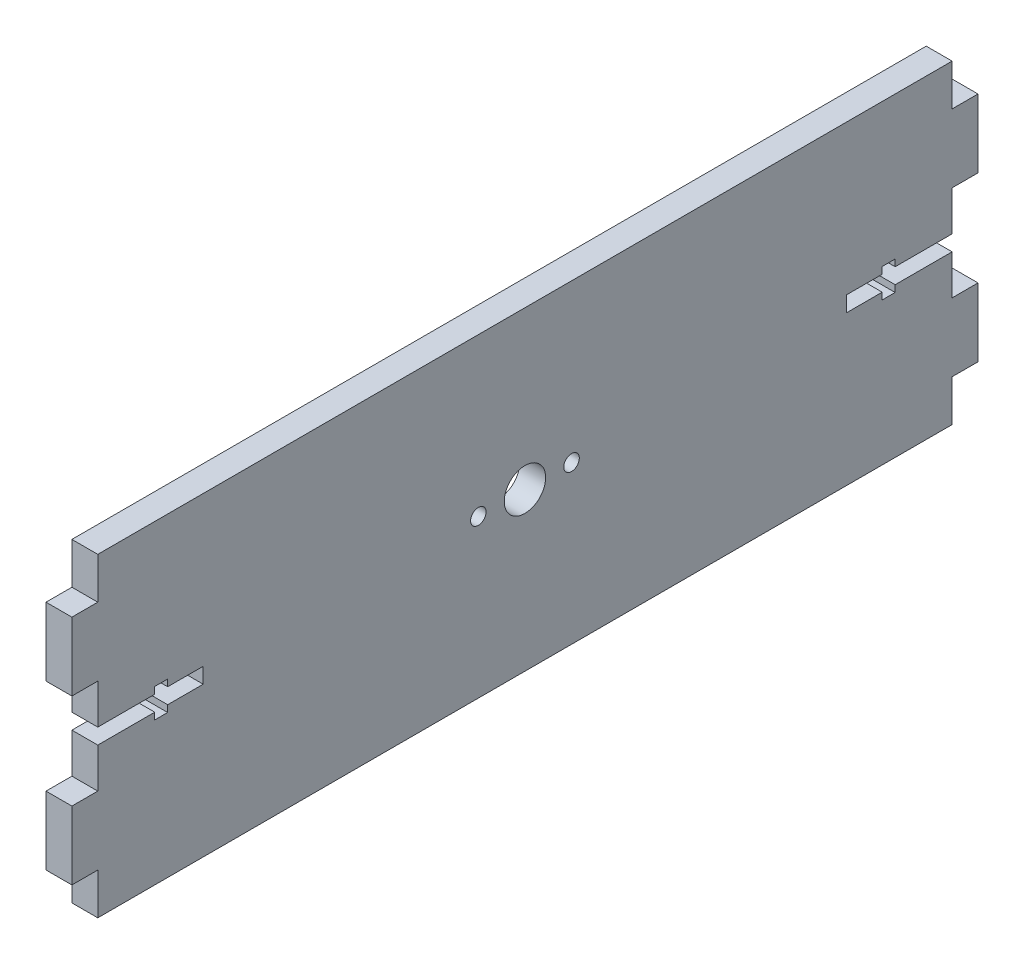
SolidWorks part; units mm, degrees
ref_plane "Front" through (0, 0, 0) normal (0, 0, 1) x (1, 0, 0)
ref_plane "Top" through (0, 0, 0) normal (0, 1, 0) x (1, 0, 0)
ref_plane "Right" through (0, 0, 0) normal (1, 0, 0) x (0, 0, -1)
sketch "Sketch1" plane through (0, 0, 0) normal (1, 0, 0) x (0, 0, -1)
  line L0 (70.2517, 12.4024) -> (70.2517, 25.6024)
  line L1 (-99.7483, 33.6024) -> (-99.7483, 25.6024)
  line L2 (-99.7483, 33.6024) -> (65.2517, 33.6024)
  line L3 (-17.2483, 33.6024) -> (-17.2483, -27.1976) construction
  line L4 (-99.7483, -19.1976) -> (-99.7483, -27.1976)
  line L5 (-99.7483, -19.1976) -> (-104.7483, -19.1976)
  line L6 (-104.7483, -19.1976) -> (-104.7483, -5.9976)
  line L7 (-104.7483, 12.4024) -> (-104.7483, 25.6024)
  line L8 (-99.7483, 12.4024) -> (-99.7483, 4.7024)
  line L9 (-99.7483, -5.9976) -> (-104.7483, -5.9976)
  line L10 (-79.3911, 1.7024) -> (-79.3911, 4.7024)
  line L11 (-99.7483, 1.7024) -> (-99.7483, -5.9976)
  line L12 (-99.7483, 25.6024) -> (-104.7483, 25.6024)
  line L13 (-99.7483, 12.4024) -> (-104.7483, 12.4024)
  line L14 (-86.2483, 4.7024) -> (-79.3911, 4.7024)
  line L15 (-86.2483, 0.4024) -> (-88.7483, 0.4024)
  line L16 (-86.2483, 1.7024) -> (-86.2483, 0.4024)
  line L17 (-86.2483, 6.0024) -> (-86.2483, 4.7024)
  line L18 (65.2517, -27.1976) -> (-99.7483, -27.1976)
  line L19 (54.2517, 4.7024) -> (54.2517, 6.0024)
  line L20 (-88.7483, 6.0024) -> (-86.2483, 6.0024)
  line L21 (-99.7483, 1.7024) -> (-88.7483, 1.7024)
  line L22 (-99.7483, 4.7024) -> (-88.7483, 4.7024)
  line L23 (-79.3911, 1.7024) -> (-86.2483, 1.7024)
  line L24 (-88.7483, 1.7024) -> (-88.7483, 0.4024)
  line L25 (-88.7483, 4.7024) -> (-88.7483, 6.0024)
  line L26 (54.2517, 1.7024) -> (54.2517, 0.4024)
  line L27 (44.8945, 1.7024) -> (51.7517, 1.7024)
  line L28 (65.2517, 4.7024) -> (54.2517, 4.7024)
  line L29 (65.2517, 1.7024) -> (54.2517, 1.7024)
  line L30 (54.2517, 6.0024) -> (51.7517, 6.0024)
  line L31 (51.7517, 6.0024) -> (51.7517, 4.7024)
  line L32 (51.7517, 1.7024) -> (51.7517, 0.4024)
  line L33 (51.7517, 0.4024) -> (54.2517, 0.4024)
  line L34 (51.7517, 4.7024) -> (44.8945, 4.7024)
  line L35 (65.2517, 12.4024) -> (70.2517, 12.4024)
  line L36 (65.2517, 25.6024) -> (70.2517, 25.6024)
  line L37 (65.2517, 1.7024) -> (65.2517, -5.9976)
  line L38 (44.8945, 1.7024) -> (44.8945, 4.7024)
  line L39 (65.2517, -5.9976) -> (70.2517, -5.9976)
  line L40 (65.2517, 12.4024) -> (65.2517, 4.7024)
  line L41 (70.2517, -19.1976) -> (70.2517, -5.9976)
  line L42 (65.2517, -19.1976) -> (70.2517, -19.1976)
  line L43 (65.2517, -19.1976) -> (65.2517, -27.1976)
  line L44 (65.2517, 33.6024) -> (65.2517, 25.6024)
  circle A0 centre (-17.2483, 3.2024) radius 4
  circle A1 centre (-26.2483, 3.2024) radius 1.5
  circle A2 centre (-8.2483, 3.2024) radius 1.5
extrude "Boss-Extrude1" add sketch "Sketch1" along normal blind 5
